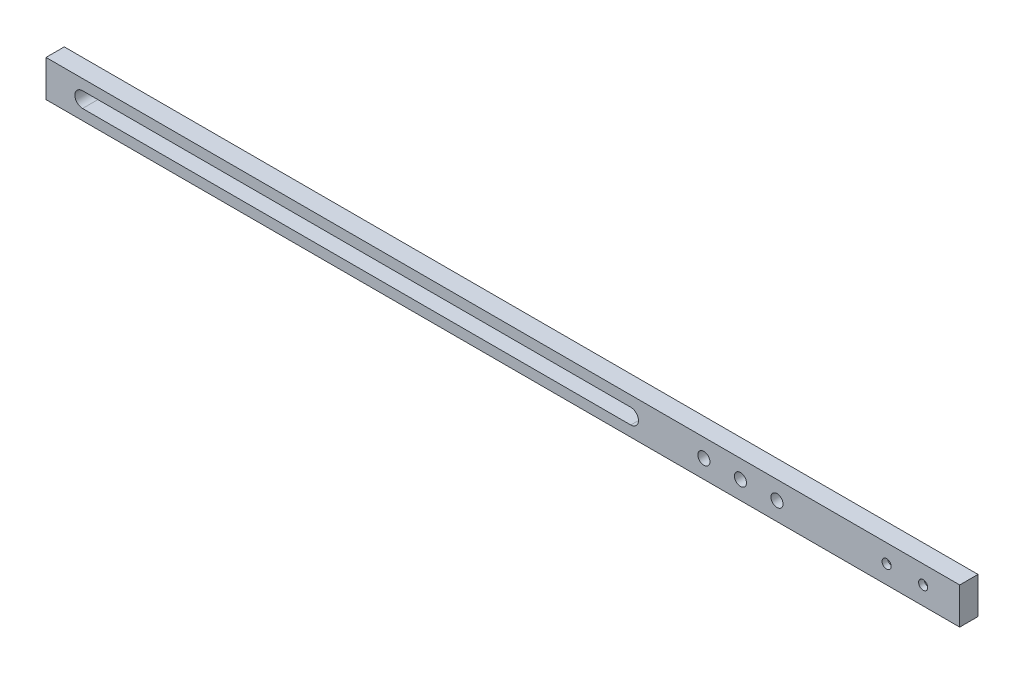
SolidWorks part; units mm, degrees
material "6061 Сплав"
ref_plane "Front" through (0, 0, 0) normal (0, 0, 1) x (1, 0, 0)
ref_plane "Top" through (0, 0, 0) normal (0, 1, 0) x (1, 0, 0)
ref_plane "Right" through (0, 0, 0) normal (1, 0, 0) x (0, 0, -1)
sketch "Эскиз1" plane through (0, 0, 0) normal (0, 0, 1) x (1, 0, 0)
  line L1 (-125, 5) -> (125, 5)
  line L2 (-125, 5) -> (-125, -5)
  line L3 (-125, -5) -> (125, -5)
  line L4 (125, 5) -> (125, -5)
  line L5 (-125, 5) -> (125, -5) construction
  line L6 (-125, -5) -> (125, 5) construction
  point P0 (0, 0)
  dimension "D1" = 250
  dimension "D2" = 10
extrude "Бобышка-Вытянуть1" add sketch "Эскиз1" along normal blind 5
sketch "Эскиз2" plane through (0, 0, 0) normal (0, 0, -1) x (-1, 0, 0)
  line L1 (-35, 2.1) -> (115, 2.1)
  line L3 (-35, -2.1) -> (115, -2.1)
  line L5 (-35, 2.1) -> (115, -2.1) construction
  line L6 (-35, -2.1) -> (115, 2.1) construction
  line L7 (-125, 5) -> (125, 5) construction
  arc A0 (-35, 2.1) -> (-35, -2.1) centre (-35, 0) ccw
  arc A1 (115, 2.1) -> (115, -2.1) centre (115, 0) cw
  point P0 (40, 0)
  dimension "D1" = 150
  dimension "D3" = 4.2
  dimension "D4" = 2.9
extrude "Вырез-Вытянуть1" cut sketch "Эскиз2" against normal blind 5
sketch "Эскиз3" plane through (0, 0, 0) normal (0, 0, -1) x (-1, 0, 0)
  line L0 (-125, -5) -> (-125, 5) construction
  line L1 (125, -5) -> (-125, -5) construction
  circle A0 centre (-115, 0) radius 1.25
  circle A1 centre (-105, 0) radius 1.25
  point P4 (-125, 0)
  dimension "D1" = 10
  dimension "D2" = 10
  dimension "D3" = 5
extrude "Вырез-Вытянуть2" cut sketch "Эскиз3" against normal blind 5
sketch "Эскиз4" plane through (0, 0, 0) normal (0, 0, -1) x (-1, 0, 0)
  circle A0 centre (-115, 0) radius 2.8
  circle A1 centre (-105, 0) radius 2.8
extrude "Вырез-Вытянуть3" cut sketch "Эскиз4" against normal blind 3.5
sketch "Эскиз5" plane through (0, 0, 0) normal (0, 0, -1) x (-1, 0, 0)
  line L0 (-125, -5) -> (-125, 5) construction
  circle A0 centre (-75, 0) radius 1.65
  circle A1 centre (-65, 0) radius 1.65
  circle A2 centre (-55, 0) radius 1.65
  point P6 (-125, 0)
  dimension "D1" = 10
  dimension "D2" = 10
  dimension "D3" = 50
extrude "Вырез-Вытянуть4" cut sketch "Эскиз5" against normal blind 10
